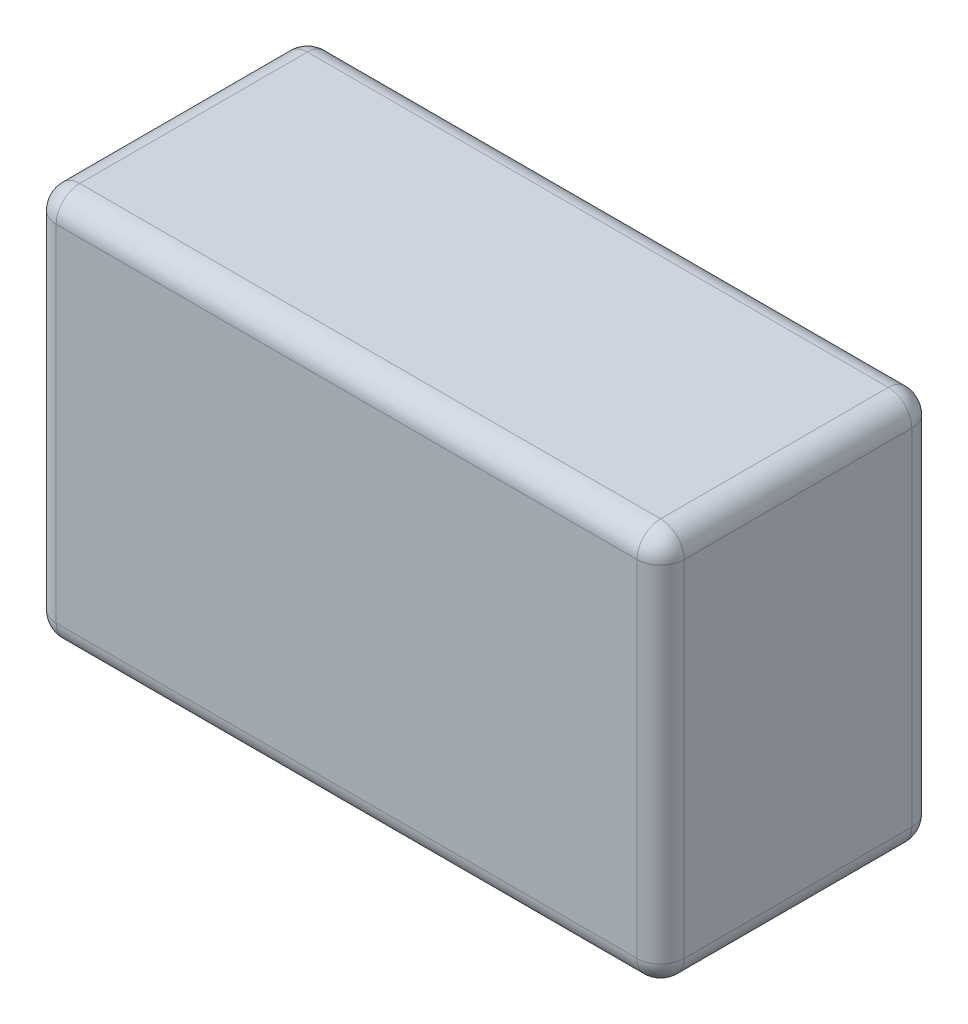
SolidWorks part; units mm, degrees
ref_plane "Front Plane" through (0, 0, 0) normal (0, 0, 1) x (1, 0, 0)
ref_plane "Top Plane" through (0, 0, 0) normal (0, 1, 0) x (1, 0, 0)
ref_plane "Right Plane" through (0, 0, 0) normal (1, 0, 0) x (0, 0, -1)
sketch "Sketch1" plane through (0, 0, 0) normal (0, 0, 1) x (1, 0, 0)
  line L1 (-39.0227, 65.8789) -> (40.9773, 65.8789)
  line L2 (-39.0227, 65.8789) -> (-39.0227, 15.8789)
  line L3 (-39.0227, 15.8789) -> (40.9773, 15.8789)
  line L4 (40.9773, 65.8789) -> (40.9773, 15.8789)
extrude "Boss-Extrude1" add sketch "Sketch1" along normal blind 35
fillet "Fillet1" radius 3 12 edges at (40.9773, 65.8789, 17.5) (0.9773, 65.8789, 35) (-39.0227, 65.8789, 17.5) (0.9773, 65.8789, 0) (40.9773, 40.8789, 0) (40.9773, 40.8789, 35) (40.9773, 15.8789, 17.5) (0.9773, 15.8789, 0) (-39.0227, 15.8789, 17.5) (-39.0227, 40.8789, 0) (-39.0227, 40.8789, 35) (0.9773, 15.8789, 35)
